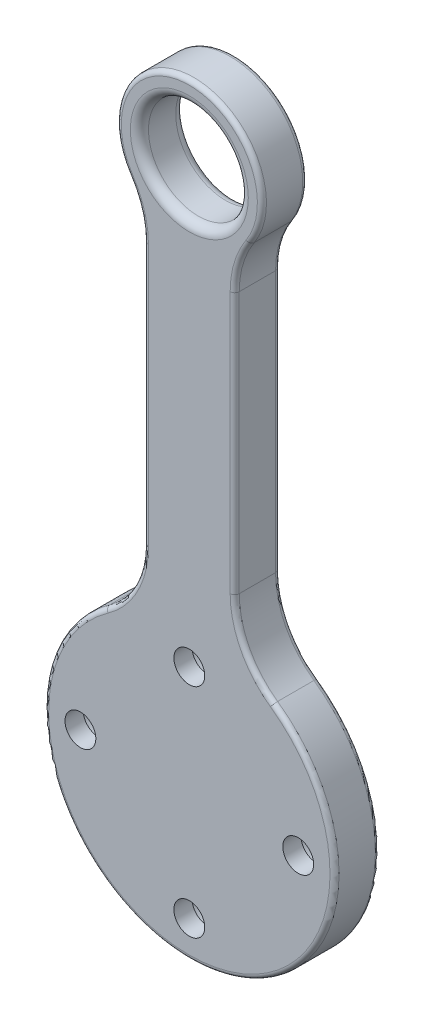
SolidWorks part; units mm, degrees
ref_plane "Front Plane" through (0, 0, 0) normal (0, 0, 1) x (1, 0, 0)
ref_plane "Top Plane" through (0, 0, 0) normal (0, 1, 0) x (1, 0, 0)
ref_plane "Right Plane" through (0, 0, 0) normal (1, 0, 0) x (0, 0, -1)
ref_plane "Plane1" through (0, 0, 5) normal (0, 0, 1) x (1, 0, 0)
sketch "Sketch1" plane through (0, 0, 5) normal (0, 0, 1) x (1, 0, 0)
  line L0 (-5, 53.755) -> (-5, 13.0767)
  line L1 (5, 13.0767) -> (5, 53.755)
  line L2 (-5, 39.7889) -> (5, 39.7889) construction
  arc A0 (-5, 13.0767) -> (5, 13.0767) centre (0, 0) ccw
  arc A1 (5, 53.755) -> (-5, 53.755) centre (0, 60) ccw
  point P6 (0, 39.7889)
  dimension "D2" = 14
  dimension "D3" = 8
  dimension "D1" = 60
  dimension "D4" = 10
extrude "Boss-Extrude1" add sketch "Sketch1" against normal blind 5
ref_plane "Plane2" through (0, 60, 0) normal (0, -1, 0) x (1, 0, 0)
sketch "Sketch2" plane through (0, 60, 0) normal (0, -1, 0) x (1, 0, 0)
  line L0 (3.5, 5) -> (0, 5)
  line L1 (0, 5) -> (0, 0)
  line L2 (0, 0) -> (4.3, 0)
  line L3 (4.3, 0) -> (2.5, 1.8)
  line L4 (2.5, 1.8) -> (2.5, 2)
  line L5 (2.5, 2) -> (3.5, 2)
  line L6 (3.5, 2) -> (3.5, 5)
  line L7 (0, 5) -> (0, 0) construction
revolve "Cut-Revolve1" cut sketch "Sketch2" angle 360 about L7
sketch "Sketch8" plane through (0, 0, 0) normal (0, 0, -1) x (-1, 0, 0)
  circle A0 centre (0, 0) radius 16
  dimension "D1" = 32
extrude "Boss-Extrude2" add sketch "Sketch8" against normal up to vertex (5 mm away)
hole_wizard "CBORE for M3 Hex Head Machine Screw0" positions "Sketch4" profile "Sketch3" counterbore size "M3" standard "ANSI Metric" end condition through all
sketch "Sketch4" plane through (0, 0, 0) normal (0, 0, -1) x (-1, 0, 0)
  line L0 (12, 0) -> (0, 0) construction
  line L1 (0, 0) -> (-12, 0) construction
  line L3 (0, 12) -> (0, 0) construction
  line L4 (0, 0) -> (0, -12) construction
  point P0 (0, 12)
  point P1 (12, 0)
  point P2 (-12, 0)
  point P3 (0, -12)
  dimension "D1" = 12
sketch "Sketch3" plane through (0, 12, 0) normal (1, 0, 0) x (0, 1, 0)
  line L0 (0, 0) -> (0, 5)
  line L1 (0, 5) -> (1.7, 5)
  line L3 (1.7, 5) -> (1.7, 3)
  line L4 (1.7, 3) -> (3.25, 3)
  line L5 (3.25, 3) -> (3.25, 0)
  line L7 (3.25, 0) -> (0, 0)
  line L11 (0, -6.35) -> (0, 107.95) construction
  dimension "Thru Hole Dia." = 3.4
  dimension "Thru Hole Depth" = 5
  dimension "C'Bore Dia." = 6.5
  dimension "C'Bore Depth" = 3
fillet "Fillet1" radius 10 4 edges at (-5, 53.755, 2.5) (5, 53.755, 2.5) (5, 15.1987, 2.5) (-5, 15.1987, 2.5)
sketch "Sketch7" plane through (0, 0, 0) normal (0, 0, -1) x (-1, 0, 0)
  circle A0 centre (0, 60) radius 5.5
  circle A1 centre (0, 60) radius 4.3 construction
  dimension "D1" = 11
extrude "Cut-Extrude1" cut sketch "Sketch7" against normal through all
fillet "Fillet2" radius 1 2 edges at (-5.5, 60, 5) (-5.5, 60, 0)
fillet "Fillet3" radius 0.5 16 edges at (6.1205, 16.6374, 0) (6.1205, 16.6374, 5) (5, 35.6434, 5) (5, 35.6434, 0) (5.4257, 52.9369, 0) (5.4257, 52.9369, 5) (0, 68, 0) (0, 68, 5) (-5.4257, 52.9369, 0) (-5.4257, 52.9369, 5) (-5, 35.6434, 0) (-5, 35.6434, 5) (-6.1205, 16.6374, 5) (-6.1205, 16.6374, 0) (0, -16, 0) (0, -16, 5)
